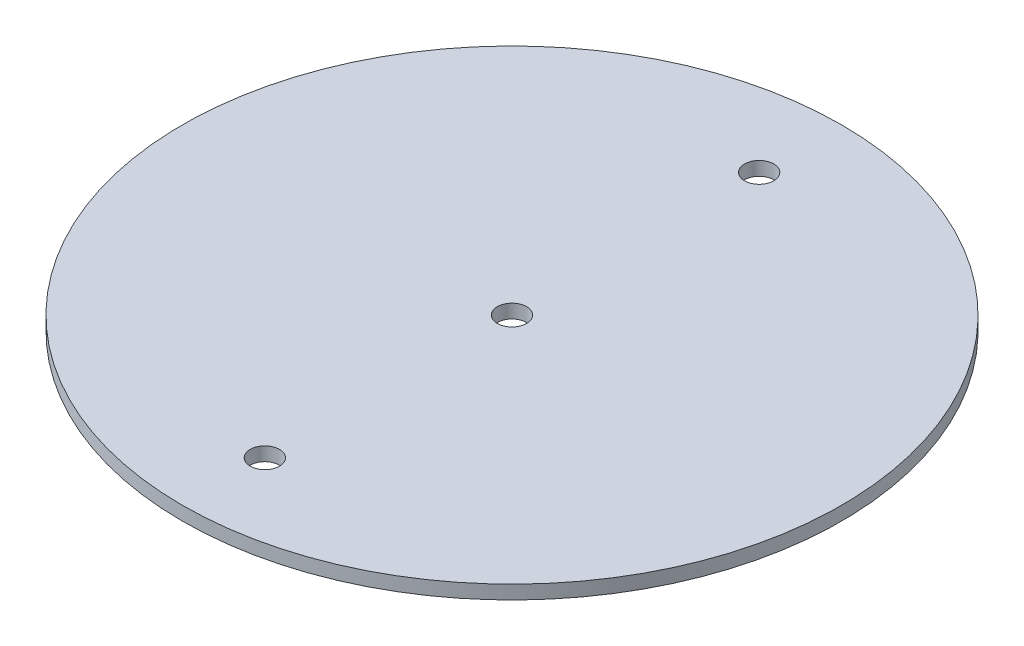
SolidWorks part; units mm, degrees
material "G10"
ref_plane "Front Plane" through (0, 0, 0) normal (0, 0, 1) x (1, 0, 0)
ref_plane "Top Plane" through (0, 0, 0) normal (0, 1, 0) x (1, 0, 0)
ref_plane "Right Plane" through (0, 0, 0) normal (1, 0, 0) x (0, 0, -1)
sketch "Sketch2" plane through (0, 0, 0) normal (0, 1, 0) x (1, 0, 0)
  circle A0 centre (0, 0) radius 76.2
  dimension "D1" = 152.4
extrude "Boss-Extrude1" add sketch "Sketch2" along normal blind 3.175
hole_wizard "1/4 Clearance Hole1" positions "Sketch3" profile "Sketch4" hole size "1/4" standard "ANSI Inch" end condition through all
sketch "Sketch3" plane through (0, 3.175, 0) normal (0, 1, 0) x (1, 0, 0)
  point P2 (0, 57.15)
  point P4 (0, -57.15)
  dimension "D1" = 57.15
  dimension "D2" = 57.15
sketch "Sketch4" plane through (0, 3.175, -57.15) normal (1, 0, 0) x (0, 0, 1)
  line L0 (0, 0) -> (0, 3.175)
  line L1 (0, 3.175) -> (3.3782, 3.175)
  line L2 (3.3782, 3.175) -> (3.3782, 0)
  line L5 (3.3782, 0) -> (0, 0)
  line L11 (0, -6.35) -> (0, 107.95) construction
  dimension "Thru Hole Dia." = 6.7564
  dimension "Thru Hole Depth" = 3.175
hole_wizard "1/4 Clearance Hole2" positions "Sketch5" profile "Sketch6" hole size "1/4" standard "ANSI Inch" end condition through all
sketch "Sketch5" plane through (0, 3.175, 0) normal (0, 1, 0) x (1, 0, 0)
  point P0 (0, 0)
sketch "Sketch6" plane through (0, 3.175, 0) normal (1, 0, 0) x (0, 0, 1)
  line L0 (0, 0) -> (0, 3.175)
  line L1 (0, 3.175) -> (3.3782, 3.175)
  line L2 (3.3782, 3.175) -> (3.3782, 0)
  line L5 (3.3782, 0) -> (0, 0)
  line L11 (0, -6.35) -> (0, 107.95) construction
  dimension "Thru Hole Dia." = 6.7564
  dimension "Thru Hole Depth" = 3.175
equation "\"airframeInnerDiameter\"= 6in"
equation "\"recoveryBayInnerDiameter\"= 5.888in"
equation "\"spacing\"= 4.5"
equation "\"D1@Sketch2\"    = \"airframeInnerDiameter\""
equation "\"D1@Boss-Extrude1\"=0.125"
equation "\"D1@Sketch3\"=\"spacing\"/2"
equation "\"D2@Sketch3\"=\"spacing\"/2"
